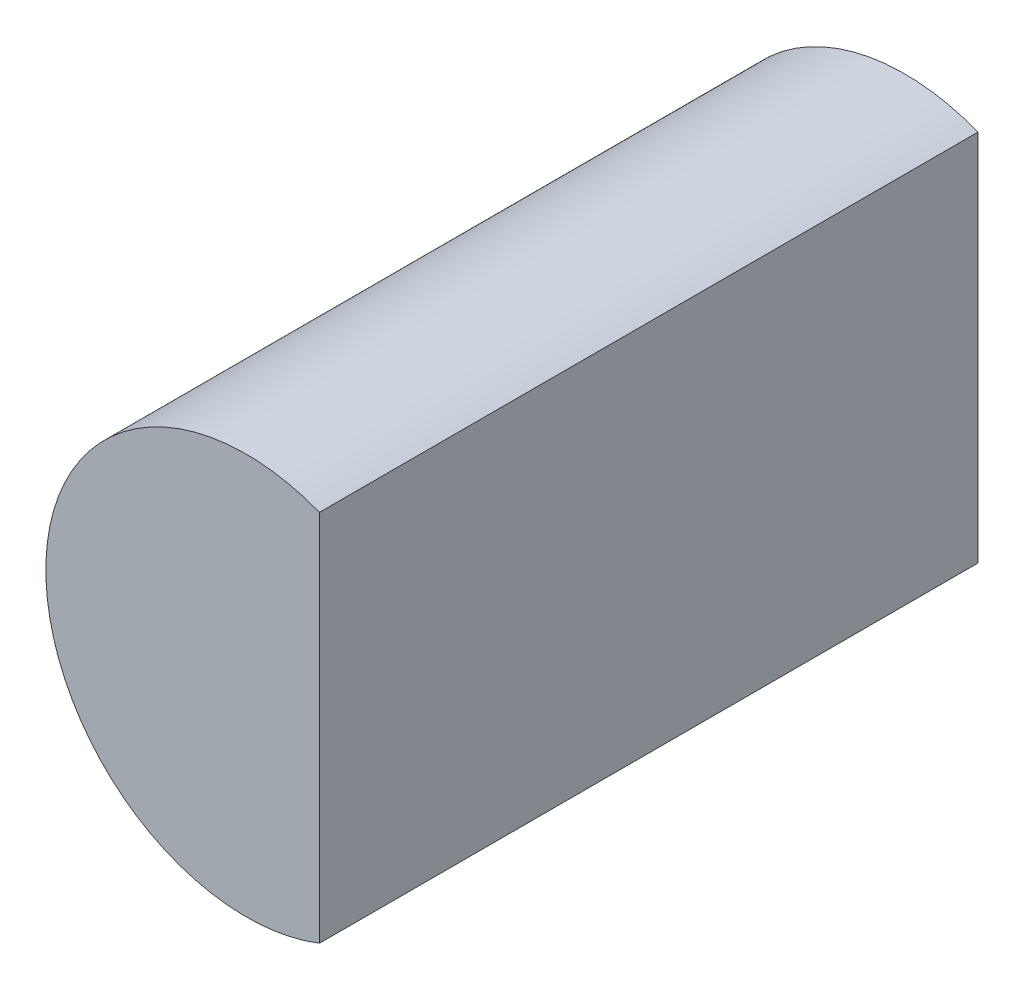
SolidWorks part; units mm, degrees
ref_plane "前视基准面" through (0, 0, 0) normal (0, 0, 1) x (1, 0, 0)
ref_plane "上视基准面" through (0, 0, 0) normal (0, 1, 0) x (1, 0, 0)
ref_plane "右视基准面" through (0, 0, 0) normal (1, 0, 0) x (0, 0, -1)
other "Configuration Table"
sketch "草图1" plane through (0, 0, 0) normal (0, 0, 1) x (1, 0, 0)
  line L0 (2, -5.1) -> (2, 5.1)
  arc A0 (2, 5.1) -> (2, -5.1) centre (0, 0) ccw
extrude "凸台-拉伸1" add sketch "草图1" along normal blind 18
